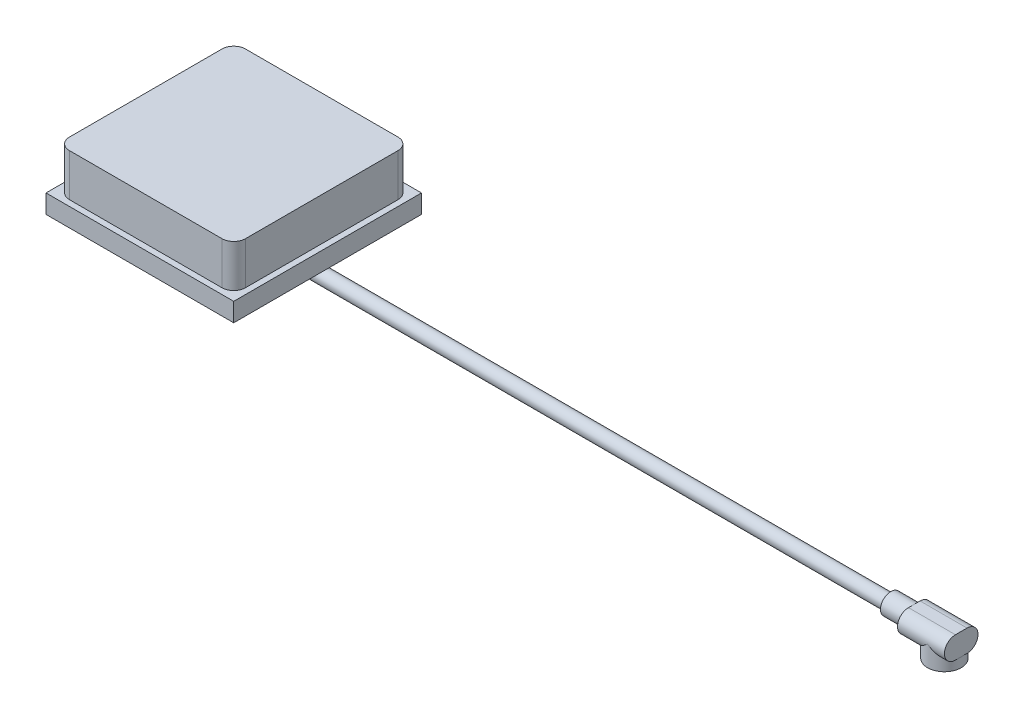
SolidWorks part; units mm, degrees
ref_plane "Front Plane" through (0, 0, 0) normal (0, 0, 1) x (1, 0, 0)
ref_plane "Top Plane" through (0, 0, 0) normal (0, 1, 0) x (1, 0, 0)
ref_plane "Right Plane" through (0, 0, 0) normal (1, 0, 0) x (0, 0, -1)
sketch "Sketch1" plane through (0, 0, 0) normal (0, 1, 0) x (1, 0, 0)
  line L1 (-8, -8) -> (8, -8)
  line L2 (-8, -8) -> (-8, 8)
  line L3 (-8, 8) -> (8, 8)
  line L4 (8, -8) -> (8, 8)
  line L5 (-8, -8) -> (8, 8) construction
  line L6 (-8, 8) -> (8, -8) construction
  point P0 (0, 0)
  dimension "D1" = 16
  dimension "D2" = 16
extrude "Boss-Extrude1" add sketch "Sketch1" along normal blind 1.5875
sketch "Sketch2" plane through (0, 1.5875, 0) normal (0, 1, 0) x (1, 0, 0)
  line L1 (-6.5, -7.5) -> (6.5, -7.5)
  line L2 (-7.5, -6.5) -> (-7.5, 6.5)
  line L3 (-6.5, 7.5) -> (6.5, 7.5)
  line L4 (7.5, -6.5) -> (7.5, 6.5)
  line L5 (-7.5, -7.5) -> (7.5, 7.5) construction
  line L6 (-7.5, 7.5) -> (7.5, -7.5) construction
  arc A0 (-7.5, -6.5) -> (-6.5, -7.5) centre (-6.5, -6.5) ccw
  arc A1 (6.5, -7.5) -> (7.5, -6.5) centre (6.5, -6.5) ccw
  arc A2 (7.5, 6.5) -> (6.5, 7.5) centre (6.5, 6.5) ccw
  arc A3 (-6.5, 7.5) -> (-7.5, 6.5) centre (-6.5, 6.5) ccw
  point P0 (0, 0)
  dimension "D3" = 1
  dimension "D1" = 15
  dimension "D2" = 15
extrude "Boss-Extrude2" add sketch "Sketch2" along normal blind 3.625
sketch "Sketch4" plane through (0, 0, 0) normal (0, -1, 0) x (1, 0, 0)
  line L0 (8, -8) -> (-8, -8) construction
  line L1 (5, 6) -> (-5, 6)
  line L2 (6, 5) -> (6, -5)
  line L3 (5, -6) -> (-5, -6)
  line L4 (-6, 5) -> (-6, -5)
  line L5 (6, 6) -> (-6, -6) construction
  line L6 (6, -6) -> (-6, 6) construction
  line L7 (-8, -8) -> (-8, 8) construction
  line L8 (6, -5) -> (5, -6)
  line L9 (-5, -6) -> (-6, -5)
  line L10 (-5, 6) -> (-6, 5)
  line L11 (6, 5) -> (5, 6)
  point P0 (0, 0)
  dimension "D1" = 2
  dimension "D2" = 2
extrude "Boss-Extrude3" add sketch "Sketch4" along normal blind 1.5875
sketch "Sketch5" plane through (6, 0, 0) normal (1, 0, 0) x (0, 0, -1)
  circle A0 centre (0, -0.7117) radius 0.5994
  point P2 (0, -0.7117)
extrude "Boss-Extrude6" add sketch "Sketch5" along normal blind 50
sketch "Sketch6" plane through (56, 0, 0) normal (1, 0, 0) x (0, 0, -1)
  circle A0 centre (0, -0.7117) radius 0.881
extrude "Boss-Extrude7" add sketch "Sketch6" along normal blind 2
sketch "Sketch7" plane through (58, 0, 0) normal (1, 0, 0) x (0, 0, -1)
  line L0 (-0.494, -0.7117) -> (0.494, -0.7117) construction
  line L1 (-0.494, 0.2254) -> (0.494, 0.2254)
  line L2 (-0.494, -1.6489) -> (0.494, -1.6489)
  arc A0 (-0.494, 0.2254) -> (-0.494, -1.6489) centre (-0.494, -0.7117) ccw
  arc A1 (0.494, -1.6489) -> (0.494, 0.2254) centre (0.494, -0.7117) ccw
  point P2 (0, -0.7117)
  point P8 (0.7937, -0.7117)
  point P9 (0.494, -0.7117)
extrude "Boss-Extrude8" add sketch "Sketch7" along normal blind 4
ref_plane "Plane1" through (0, -0.7117, 0) normal (0, 1, 0) x (1, 0, 0)
sketch "Sketch8" plane through (0, -0.7117, 0) normal (0, -1, 0) x (1, 0, 0)
  line L0 (62, 1.4311) -> (58, 1.4311) construction
  line L1 (62, 0) -> (60.5689, 0) construction
  line L2 (62, -0.494) -> (62, 0.494) construction
  circle A0 centre (60.5689, 0) radius 1.4311
extrude "Boss-Extrude9" add sketch "Sketch8" along normal blind 1.75
sketch "Sketch9" plane through (0, -2.4617, 0) normal (0, -1, 0) x (-1, 0, 0)
  circle A0 centre (-60.5689, 0) radius 1.0268
  circle A1 centre (-60.5689, 0) radius 0.3869
  circle A2 centre (-60.5689, 0) radius 1.4311 construction
extrude "Cut-Extrude1" cut sketch "Sketch9" against normal blind 0.5
